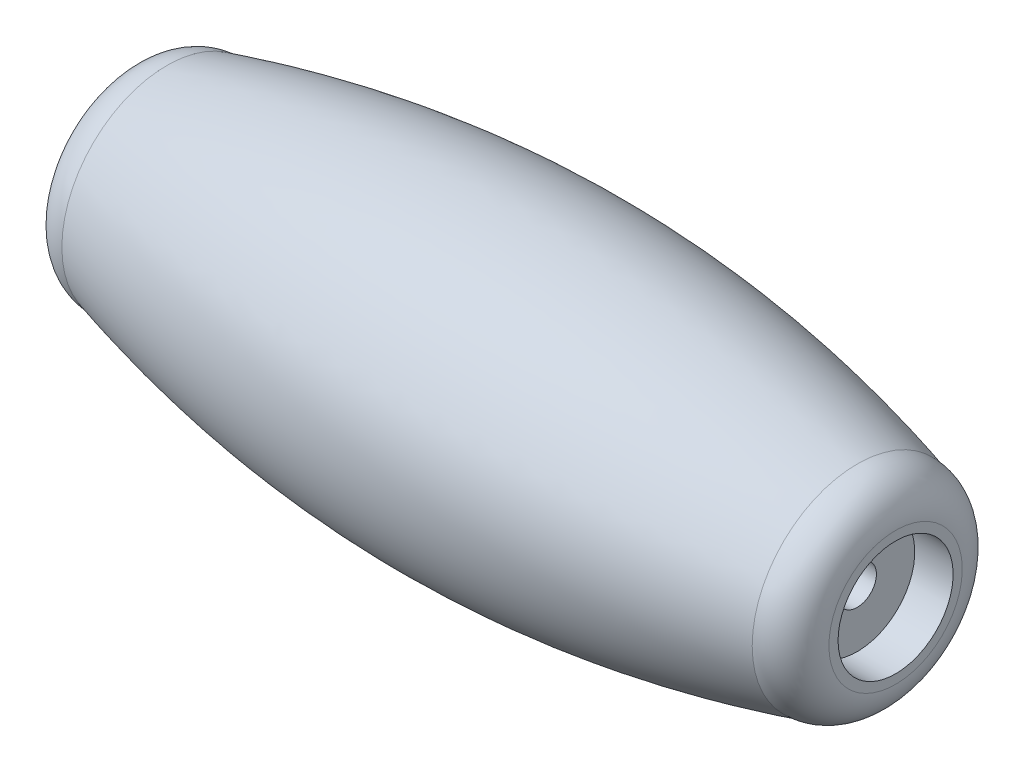
SolidWorks part; units mm, degrees
ref_plane "Front Plane" through (0, 0, 0) normal (0, 0, 1) x (1, 0, 0)
ref_plane "Top Plane" through (0, 0, 0) normal (0, 1, 0) x (1, 0, 0)
ref_plane "Right Plane" through (0, 0, 0) normal (1, 0, 0) x (0, 0, -1)
sketch "Sketch2" plane through (0, 0, 0) normal (0, 0, 1) x (1, 0, 0)
  line L0 (-15, 0) -> (15, 0) construction
  line L1 (0, 0) -> (0, 6) construction
  line L2 (0, 0.75) -> (15, 0.75) construction
  line L3 (13.5, 0.75) -> (-13.5, 0.75)
  line L4 (15, 2.25) -> (13.5, 2.25)
  line L5 (13.5, 2.25) -> (13.5, 0.75)
  line L6 (15, 2.25) -> (15, 2.6083)
  line L7 (-13.5, 2.25) -> (-13.5, 0.75)
  line L8 (-15, 2.25) -> (-13.5, 2.25)
  line L9 (-15, 2.25) -> (-15, 2.6083)
  circle A0 centre (13.5, 2.6083) radius 1.5 construction
  arc A1 (13.5, 4.1083) -> (15, 2.6083) centre (13.5, 2.6083) cw
  arc A2 (-13.5, 4.1083) -> (-15, 2.6083) centre (-13.5, 2.6083) ccw
  spline S0 degree 2 poles (-13.5, 4.1083) (0, 7.8917) (13.5, 4.1083) knots 0 0 0 1 1 1
  dimension "D1" = 15
  dimension "D2" = 6
  dimension "D3" = 0.75
  dimension "D4" = 1.5
  dimension "D5" = 1.5
revolve "Revolve1" add sketch "Sketch2" angle 360 about L0
